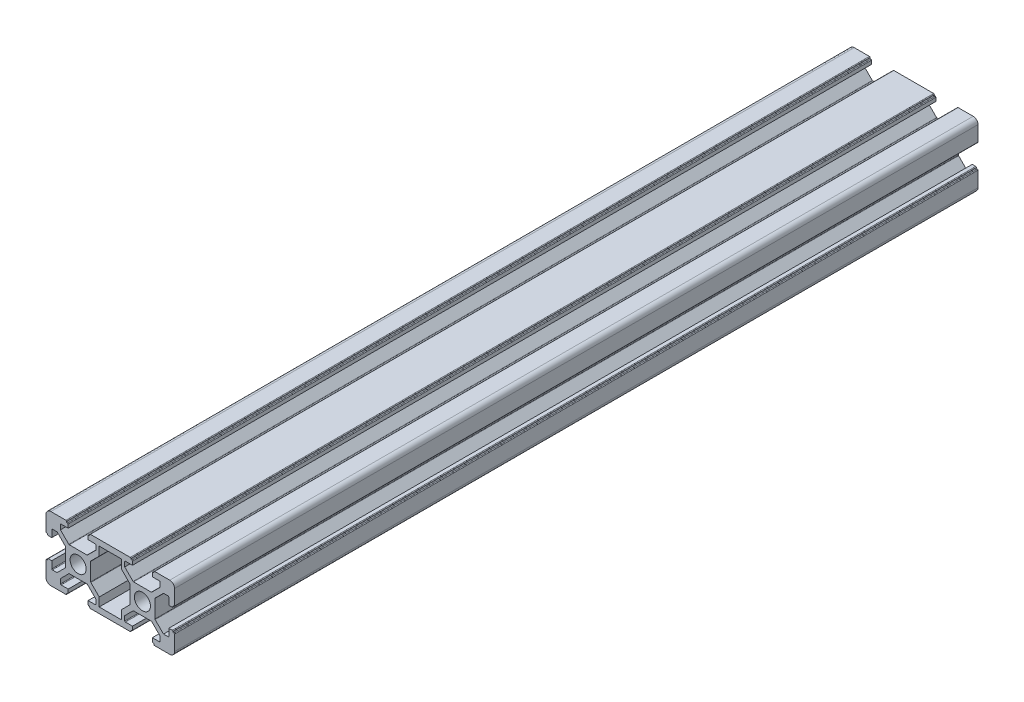
SolidWorks part; units mm, degrees
ref_plane "前视基准面" through (0, 0, 0) normal (0, 0, 1) x (1, 0, 0)
ref_plane "上视基准面" through (0, 0, 0) normal (0, 1, 0) x (1, 0, 0)
ref_plane "右视基准面" through (0, 0, 0) normal (1, 0, 0) x (0, 0, -1)
sketch "Sketch1" plane through (0, 0, 0) normal (0, 0, 1) x (1, 0, 0)
  line L0 (-8.5, 10) -> (-3.8, 10)
  line L3 (-8.5, -10) -> (-3.8, -10)
  line L5 (-10, 8.5) -> (-10, 3.8)
  line L6 (-2.7565, 3.9) -> (2.7565, 3.9)
  line L9 (-2.7565, -3.9) -> (2.7565, -3.9)
  line L10 (3.9, 2.7565) -> (3.9, -2.7565)
  line L11 (-3.9, 2.7565) -> (-3.9, -2.7565)
  line L12 (-3.9586, -2.8979) -> (-6.5607, -5.5)
  line L13 (3.6, 9.7) -> (3.6, 9.8)
  line L14 (3.1, -8.2) -> (5.3, -8.2)
  line L15 (-2.8979, -3.9586) -> (-5.5, -6.5607)
  line L16 (-3.1, -8.2) -> (-3.1, -9.3)
  line L17 (3.1, -8.2) -> (3.1, -9.3)
  line L18 (-5.5, -6.5607) -> (-5.5, -8)
  line L19 (5.5, -6.5607) -> (5.5, -8)
  line L20 (-5.3, -8.2) -> (-3.1, -8.2)
  line L21 (-3.4, -9.5) -> (-3.3, -9.5)
  line L22 (3.8, -10) -> (8.5, -10)
  line L23 (3.3, -9.5) -> (3.4, -9.5)
  line L24 (-3.6, -9.7) -> (-3.6, -9.8)
  line L25 (3.6, -9.7) -> (3.6, -9.8)
  line L26 (-6.5607, -5.5) -> (-8, -5.5)
  line L27 (-9.7, -3.6) -> (-9.8, -3.6)
  line L28 (-9.5, -3.4) -> (-9.5, -3.3)
  line L29 (-8.2, -3.1) -> (-9.3, -3.1)
  line L30 (-8.2, -5.3) -> (-8.2, -3.1)
  line L31 (-10, -3.8) -> (-10, -8.5)
  line L33 (3.8, 10) -> (8.5, 10)
  line L34 (2.8979, -3.9586) -> (5.5, -6.5607)
  line L40 (3.9586, -2.8979) -> (6.5607, -5.5)
  line L41 (3.3, 9.5) -> (3.4, 9.5)
  line L42 (30, 8.5) -> (30, 3.8)
  line L43 (3.1, 8.2) -> (3.1, 9.3)
  line L44 (3.1, 8.2) -> (5.3, 8.2)
  line L45 (5.5, 6.5607) -> (5.5, 8)
  line L46 (2.8979, 3.9586) -> (5.5, 6.5607)
  line L52 (3.9586, 2.8979) -> (6.5607, 5.5)
  line L53 (-3.6, 9.7) -> (-3.6, 9.8)
  line L54 (-3.4, 9.5) -> (-3.3, 9.5)
  line L55 (-3.1, 8.2) -> (-3.1, 9.3)
  line L56 (-5.3, 8.2) -> (-3.1, 8.2)
  line L57 (-5.5, 6.5607) -> (-5.5, 8)
  line L58 (-2.8979, 3.9586) -> (-5.5, 6.5607)
  line L59 (-9.5, 3.4) -> (-9.5, 3.3)
  line L60 (-9.7, 3.6) -> (-9.8, 3.6)
  line L61 (-8.2, 3.1) -> (-9.3, 3.1)
  line L62 (-8.2, 5.3) -> (-8.2, 3.1)
  line L63 (-6.5607, 5.5) -> (-8, 5.5)
  line L64 (-3.9586, 2.8979) -> (-6.5607, 5.5)
  line L65 (29.7, 3.6) -> (29.8, 3.6)
  line L66 (29.5, 3.4) -> (29.5, 3.3)
  line L67 (28.2, 3.1) -> (29.3, 3.1)
  line L68 (28.2, 5.3) -> (28.2, 3.1)
  line L69 (26.5607, 5.5) -> (28, 5.5)
  line L70 (23.9586, 2.8979) -> (26.5607, 5.5)
  line L71 (23.9, 2.7565) -> (23.9, -2.7565)
  line L72 (23.9586, -2.8979) -> (26.5607, -5.5)
  line L73 (26.5607, -5.5) -> (28, -5.5)
  line L74 (28.2, -5.3) -> (28.2, -3.1)
  line L75 (28.2, -3.1) -> (29.3, -3.1)
  line L76 (29.5, -3.4) -> (29.5, -3.3)
  line L77 (29.7, -3.6) -> (29.8, -3.6)
  line L78 (30, -3.8) -> (30, -8.5)
  line L79 (28.5, -10) -> (23.8, -10)
  line L80 (23.6, -9.7) -> (23.6, -9.8)
  line L81 (23.4, -9.5) -> (23.3, -9.5)
  line L82 (23.1, -8.2) -> (23.1, -9.3)
  line L83 (25.3, -8.2) -> (23.1, -8.2)
  line L84 (25.5, -6.5607) -> (25.5, -8)
  line L85 (22.8979, -3.9586) -> (25.5, -6.5607)
  line L86 (22.7565, -3.9) -> (17.2435, -3.9)
  line L87 (17.1021, -3.9586) -> (14.5, -6.5607)
  line L88 (14.5, -6.5607) -> (14.5, -8)
  line L89 (16.9, -8.2) -> (14.7, -8.2)
  line L90 (16.9, -8.2) -> (16.9, -9.3)
  line L91 (16.7, -9.5) -> (16.6, -9.5)
  line L92 (16.4, -9.7) -> (16.4, -9.8)
  line L93 (16.2, -10) -> (11.5, -10)
  line L94 (13.4393, 5.5) -> (13.4393, 8.2)
  line L96 (6.5607, 5.5) -> (6.5607, 8.2)
  line L97 (6.5607, 8.2) -> (13.4393, 8.2)
  line L99 (16.0414, -2.8979) -> (13.4393, -5.5)
  line L100 (16.1, 2.7565) -> (16.1, -2.7565)
  line L101 (16.0414, 2.8979) -> (13.4393, 5.5)
  line L107 (16.2, 10) -> (11.5, 10)
  line L108 (16.4, 9.7) -> (16.4, 9.8)
  line L109 (16.7, 9.5) -> (16.6, 9.5)
  line L110 (16.9, 8.2) -> (16.9, 9.3)
  line L111 (16.9, 8.2) -> (14.7, 8.2)
  line L112 (14.5, 6.5607) -> (14.5, 8)
  line L113 (17.1021, 3.9586) -> (14.5, 6.5607)
  line L114 (22.7565, 3.9) -> (17.2435, 3.9)
  line L115 (22.8979, 3.9586) -> (25.5, 6.5607)
  line L116 (25.5, 6.5607) -> (25.5, 8)
  line L117 (25.3, 8.2) -> (23.1, 8.2)
  line L118 (23.1, 8.2) -> (23.1, 9.3)
  line L119 (23.4, 9.5) -> (23.3, 9.5)
  line L120 (23.6, 9.7) -> (23.6, 9.8)
  line L121 (28.5, 10) -> (23.8, 10)
  line L122 (13.4393, -5.5) -> (13.4393, -8.2)
  line L124 (6.5607, -5.5) -> (6.5607, -8.2)
  line L125 (6.5607, -8.2) -> (13.4393, -8.2)
  line L127 (8.5, 10) -> (11.5, 10)
  line L128 (8.5, -10) -> (11.5, -10)
  arc A3 (-8.5, -10) -> (-10, -8.5) centre (-8.5, -8.5) cw
  arc A4 (-10, 8.5) -> (-8.5, 10) centre (-8.5, 8.5) cw
  arc A5 (3.4, -9.5) -> (3.6, -9.7) centre (3.4, -9.7) cw
  arc A6 (3.8, -10) -> (3.6, -9.8) centre (3.8, -9.8) cw
  arc A7 (3.3, -9.5) -> (3.1, -9.3) centre (3.3, -9.3) cw
  arc A8 (5.3, -8.2) -> (5.5, -8) centre (5.3, -8) ccw
  arc A9 (-3.9, -2.7565) -> (-3.9586, -2.8979) centre (-4.1, -2.7565) cw
  arc A10 (-3.9, 2.7565) -> (-3.9586, 2.8979) centre (-4.1, 2.7565) ccw
  arc A11 (-2.7565, 3.9) -> (-2.8979, 3.9586) centre (-2.7565, 4.1) cw
  arc A12 (2.7565, 3.9) -> (2.8979, 3.9586) centre (2.7565, 4.1) ccw
  arc A13 (3.9586, 2.8979) -> (3.9, 2.7565) centre (4.1, 2.7565) ccw
  arc A14 (3.9, -2.7565) -> (3.9586, -2.8979) centre (4.1, -2.7565) ccw
  arc A15 (-2.8979, -3.9586) -> (-2.7565, -3.9) centre (-2.7565, -4.1) cw
  arc A16 (2.7565, -3.9) -> (2.8979, -3.9586) centre (2.7565, -4.1) cw
  arc A17 (-3.6, -9.8) -> (-3.8, -10) centre (-3.8, -9.8) cw
  arc A18 (-3.3, -9.5) -> (-3.1, -9.3) centre (-3.3, -9.3) ccw
  arc A19 (-3.6, -9.7) -> (-3.4, -9.5) centre (-3.4, -9.7) cw
  arc A20 (-8.2, 5.3) -> (-8, 5.5) centre (-8, 5.3) cw
  arc A23 (-8.2, -5.3) -> (-8, -5.5) centre (-8, -5.3) ccw
  arc A24 (-5.3, -8.2) -> (-5.5, -8) centre (-5.3, -8) cw
  arc A31 (3.1, 9.3) -> (3.3, 9.5) centre (3.3, 9.3) cw
  arc A32 (3.6, 9.8) -> (3.8, 10) centre (3.8, 9.8) cw
  arc A33 (3.6, 9.7) -> (3.4, 9.5) centre (3.4, 9.7) cw
  arc A34 (-3.8, 10) -> (-3.6, 9.8) centre (-3.8, 9.8) cw
  arc A35 (-3.3, 9.5) -> (-3.1, 9.3) centre (-3.3, 9.3) cw
  arc A36 (-3.4, 9.5) -> (-3.6, 9.7) centre (-3.4, 9.7) cw
  arc A37 (5.5, 8) -> (5.3, 8.2) centre (5.3, 8) ccw
  arc A38 (-5.5, 8) -> (-5.3, 8.2) centre (-5.3, 8) cw
  arc A39 (-10, 3.8) -> (-9.8, 3.6) centre (-9.8, 3.8) ccw
  arc A40 (-9.5, 3.3) -> (-9.3, 3.1) centre (-9.3, 3.3) ccw
  arc A41 (-9.7, 3.6) -> (-9.5, 3.4) centre (-9.7, 3.4) cw
  arc A42 (-10, -3.8) -> (-9.8, -3.6) centre (-9.8, -3.8) cw
  arc A43 (-9.5, -3.3) -> (-9.3, -3.1) centre (-9.3, -3.3) cw
  arc A44 (-9.5, -3.4) -> (-9.7, -3.6) centre (-9.7, -3.4) cw
  arc A45 (30, 8.5) -> (28.5, 10) centre (28.5, 8.5) ccw
  arc A46 (30, 3.8) -> (29.8, 3.6) centre (29.8, 3.8) cw
  arc A47 (29.7, 3.6) -> (29.5, 3.4) centre (29.7, 3.4) ccw
  arc A48 (29.5, 3.3) -> (29.3, 3.1) centre (29.3, 3.3) cw
  arc A49 (28.2, 5.3) -> (28, 5.5) centre (28, 5.3) ccw
  arc A50 (23.9, 2.7565) -> (23.9586, 2.8979) centre (24.1, 2.7565) cw
  arc A51 (23.9, -2.7565) -> (23.9586, -2.8979) centre (24.1, -2.7565) ccw
  arc A52 (28.2, -5.3) -> (28, -5.5) centre (28, -5.3) cw
  arc A53 (29.5, -3.3) -> (29.3, -3.1) centre (29.3, -3.3) ccw
  arc A54 (29.5, -3.4) -> (29.7, -3.6) centre (29.7, -3.4) ccw
  arc A55 (30, -3.8) -> (29.8, -3.6) centre (29.8, -3.8) ccw
  arc A56 (28.5, -10) -> (30, -8.5) centre (28.5, -8.5) ccw
  arc A57 (23.6, -9.8) -> (23.8, -10) centre (23.8, -9.8) ccw
  arc A58 (23.6, -9.7) -> (23.4, -9.5) centre (23.4, -9.7) ccw
  arc A59 (23.3, -9.5) -> (23.1, -9.3) centre (23.3, -9.3) cw
  arc A60 (25.3, -8.2) -> (25.5, -8) centre (25.3, -8) ccw
  arc A61 (22.8979, -3.9586) -> (22.7565, -3.9) centre (22.7565, -4.1) ccw
  arc A62 (17.2435, -3.9) -> (17.1021, -3.9586) centre (17.2435, -4.1) ccw
  arc A63 (14.7, -8.2) -> (14.5, -8) centre (14.7, -8) cw
  arc A64 (16.7, -9.5) -> (16.9, -9.3) centre (16.7, -9.3) ccw
  arc A65 (16.6, -9.5) -> (16.4, -9.7) centre (16.6, -9.7) ccw
  arc A66 (16.2, -10) -> (16.4, -9.8) centre (16.2, -9.8) ccw
  arc A72 (16.1, -2.7565) -> (16.0414, -2.8979) centre (15.9, -2.7565) cw
  arc A73 (16.0414, 2.8979) -> (16.1, 2.7565) centre (15.9, 2.7565) cw
  arc A79 (16.4, 9.8) -> (16.2, 10) centre (16.2, 9.8) ccw
  arc A80 (16.4, 9.7) -> (16.6, 9.5) centre (16.6, 9.7) ccw
  arc A81 (16.9, 9.3) -> (16.7, 9.5) centre (16.7, 9.3) ccw
  arc A82 (14.5, 8) -> (14.7, 8.2) centre (14.7, 8) cw
  arc A83 (17.2435, 3.9) -> (17.1021, 3.9586) centre (17.2435, 4.1) cw
  arc A84 (22.7565, 3.9) -> (22.8979, 3.9586) centre (22.7565, 4.1) ccw
  arc A85 (25.5, 8) -> (25.3, 8.2) centre (25.3, 8) ccw
  arc A86 (23.3, 9.5) -> (23.1, 9.3) centre (23.3, 9.3) ccw
  arc A87 (23.4, 9.5) -> (23.6, 9.7) centre (23.4, 9.7) ccw
  arc A88 (23.8, 10) -> (23.6, 9.8) centre (23.8, 9.8) ccw
  point P11 (3.9, 3.9)
  point P19 (3.3697, 4.4303)
  point P20 (-10.6428, -10.6428)
  point P25 (-11.1731, -10.1124)
  point P26 (4.4303, 3.3697)
  point P28 (-10.1124, -11.1731)
  dimension "D3" = 0.2
  dimension "D4" = 0.2
  dimension "D5" = 0.2
  dimension "D8" = 0.2
  dimension "D9" = 0.2
  dimension "D10" = 0.2
  dimension "D6" = 1.8
  dimension "D7" = 0.5
extrude "Boss-Extrude1" add sketch "Sketch1" along normal blind 250
ref_plane "hole" through (0, 0, 250) normal (0, 0, 1) x (1, 0, 0)
sketch "Sketch2" plane through (0, 0, 250) normal (0, 0, 1) x (1, 0, 0)
  circle A0 centre (0, 0) radius 2.5
  circle A1 centre (20, 0) radius 2.5
  dimension "D1" = 5
extrude "Cut-Extrude1" cut sketch "Sketch2" against normal through all
